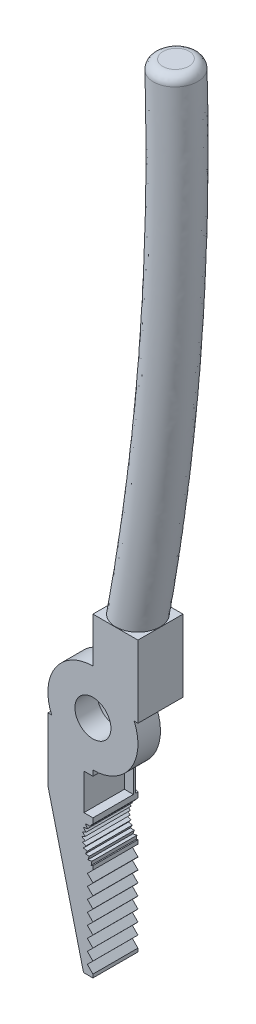
SolidWorks part; units mm, degrees
ref_plane "Front Plane" through (0, 0, 0) normal (0, 0, 1) x (1, 0, 0)
ref_plane "Top Plane" through (0, 0, 0) normal (0, 1, 0) x (1, 0, 0)
ref_plane "Right Plane" through (0, 0, 0) normal (1, 0, 0) x (0, 0, -1)
sketch "Sketch1" plane through (0, 0, 0) normal (0, 0, 1) x (1, 0, 0)
  line L0 (0, -10) -> (0, -20.3897)
  line L1 (0, -50) -> (-2.09, -50)
  line L2 (-10, -18) -> (-10, -4)
  line L3 (0, 10) -> (0, 20)
  line L4 (0, 20) -> (10, 20)
  line L5 (10, 20) -> (10, 4)
  line L6 (-10, -18) -> (-2.09, -50)
  line L7 (14.7669, 4) -> (9.1652, 4)
  line L8 (-10, -4) -> (-9.1652, -4)
  line L9 (0, -49.2488) -> (-1.2488, -48)
  line L10 (-1.2488, -48) -> (0, -46.7512)
  line L11 (-1.2488, -48) -> (0, -48) construction
  line L12 (-1.2449, -45.4965) -> (0.004, -44.2476)
  line L13 (0.004, -46.7453) -> (-1.2449, -45.4965)
  line L14 (-1.2409, -42.993) -> (0.008, -41.7441)
  line L15 (0.008, -44.2418) -> (-1.2409, -42.993)
  line L16 (-1.2369, -40.4894) -> (0.0119, -39.2406)
  line L17 (0.0119, -41.7383) -> (-1.2369, -40.4894)
  line L18 (-1.2329, -37.9859) -> (0.0159, -36.7371)
  line L19 (0.0159, -39.2348) -> (-1.2329, -37.9859)
  line L20 (-1.2289, -35.4824) -> (0.0199, -34.2336)
  line L21 (0.0199, -36.7312) -> (-1.2289, -35.4824)
  line L22 (-1.225, -32.9789) -> (0.0239, -31.73)
  line L23 (0.0239, -34.2277) -> (-1.225, -32.9789)
  line L24 (-1.221, -30.4754) -> (0.0278, -29.2265)
  line L25 (0.0278, -31.7242) -> (-1.221, -30.4754)
  line L26 (0, -31.6963) -> (0, -31.7539)
  line L27 (0, -34.2038) -> (0, -34.2535)
  line L28 (0, -36.7113) -> (0, -36.753)
  line L29 (0, -39.2188) -> (0, -39.2525)
  line L30 (0, -44.2338) -> (0, -44.2516)
  line L31 (0, -41.7263) -> (0, -41.7521)
  line L32 (0, -46.7413) -> (0, -48)
  line L33 (0, -49.2488) -> (0, -50)
  line L35 (-1.6651, -21.1327) -> (-1.2242, -21.903)
  line L36 (-1.6651, -21.1327) -> (-0.6651, -21.1365)
  line L37 (-2.0988, -22.0539) -> (-1.2242, -21.903)
  line L38 (-2.0988, -22.0539) -> (-1.5309, -22.7359)
  line L39 (-2.366, -23.0363) -> (-1.5309, -22.7359)
  line L40 (-2.366, -23.0363) -> (-1.6883, -23.6094)
  line L41 (-2.4585, -24.0503) -> (-1.6883, -23.6094)
  line L42 (-2.4585, -24.0503) -> (-1.6916, -24.4969)
  line L43 (-2.3736, -25.0649) -> (-1.6916, -24.4969)
  line L44 (-2.3736, -25.0649) -> (-1.5407, -25.3715)
  line L45 (-2.1137, -26.0493) -> (-1.5407, -25.3715)
  line L46 (-2.1137, -26.0493) -> (-1.2403, -26.2067)
  line L47 (-1.6869, -26.9737) -> (-1.2403, -26.2067)
  line L48 (-1.6869, -26.9737) -> (-0.7993, -26.977)
  line L49 (-1.106, -27.8098) -> (-0.7993, -26.977)
  line L50 (-1.106, -27.8098) -> (-0.2314, -27.659)
  line L51 (-0.3888, -28.5325) -> (-0.2314, -27.659)
  line L52 (-0.3888, -28.5325) -> (0, -28.3926)
  line L70 (0, -28.3926) -> (0, -29.2544)
  line L71 (7.1202, -28.5604) -> (6.9502, -27.575) [skipped]
  line L72 (6.2873, -28.2538) -> (6.2877, -28.1413) [skipped]
  line L73 (6.2873, -28.2538) -> (6.1818, -28.2149) [skipped]
  line L74 (5.517, -28.6947) -> (5.4198, -28.6381) [skipped]
  line L75 (5.517, -28.6947) -> (5.537, -28.584) [skipped]
  line L76 (4.6819, -28.9951) -> (4.7207, -28.8896) [skipped]
  line L77 (4.6819, -28.9951) -> (4.596, -28.9225) [skipped]
  line L78 (3.8073, -29.146) -> (3.8638, -29.0488) [skipped]
  line L79 (3.8073, -29.146) -> (3.7353, -29.0596) [skipped]
  line L80 (2.9197, -29.1427) -> (2.9923, -29.0568) [skipped]
  line L81 (2.9197, -29.1427) -> (2.8638, -29.0451) [skipped]
  line L82 (2.0462, -28.9853) -> (2.1327, -28.9133) [skipped]
  line L83 (2.0462, -28.9853) -> (2.0082, -28.8795) [skipped]
  line L84 (1.2134, -28.6786) -> (1.311, -28.6228) [skipped]
  line L85 (1.2134, -28.6786) -> (1.1942, -28.5678) [skipped]
  line L86 (0.4464, -28.232) -> (0.4468, -28.1196) [skipped]
  circle A0 centre (0, 0) radius 10
  circle A1 centre (0, 0) radius 4
  arc A2 (-0.6651, -21.1365) -> (0, -20.3897) centre (3.3824, -24.072) cw
  point P114 (3.3824, -24.072)
  dimension "D1" = 20
  dimension "D9" = 8
  dimension "D2" = 40
  dimension "D3" = 45
  dimension "D4" = 2.09
  dimension "D5" = 2
  dimension "D6" = 4
  dimension "D7" = 4
  dimension "D8" = 8
  dimension "D12" = 60
  dimension "D15" = 1
  dimension "D16" = 17
extrude "Boss-Extrude2" add sketch "Sketch1" along normal blind 10 contours A0 L7 L5 L4 L3 | A0 A1 | L36 A2 L0 A0 L8 L2 L6 L1 L33 L9 L10 L32 L13 L12 L30 L15 L14 L31 L17 L16 L29 L19 L18 L28 L21 L20 L27 L23 L22 L26 L25 L24 L70 L52 L51 L50 L49 L48 L47 L46 L45 L44 L43 L42 L41 L40 L39 L38 L37 L35
sketch "Sketch2" plane through (0, 0, 10) normal (0, 0, 1) x (1, 0, 0)
  line L0 (0, -10) -> (0, -20.3897) construction
  line L1 (2, -19.1949) -> (-2, -19.1949)
  line L2 (2, -19.1949) -> (2, -11.1949)
  line L3 (2, -11.1949) -> (-2, -11.1949)
  line L4 (-2, -19.1949) -> (-2, -11.1949)
  line L5 (2, -19.1949) -> (-2, -11.1949) construction
  line L6 (2, -11.1949) -> (-2, -19.1949) construction
  point P0 (0, -15.1949)
  dimension "D1" = 4
  dimension "D2" = 8
extrude "Cut-Extrude1" cut sketch "Sketch2" against normal blind 9
sketch "Sketch3" plane through (0, 0, 0) normal (1, 0, 0) x (0, 0, -1)
  line L0 (0, -10) -> (0, -20.3897) construction
  line L1 (0.5, -19.1949) -> (-0.5, -19.1949)
  line L2 (0.5, -19.1949) -> (0.5, -11.1949)
  line L3 (0.5, -11.1949) -> (-0.5, -11.1949)
  line L4 (-0.5, -19.1949) -> (-0.5, -11.1949)
  line L5 (0.5, -19.1949) -> (-0.5, -11.1949) construction
  line L6 (0.5, -11.1949) -> (-0.5, -19.1949) construction
  point P0 (0, -15.1949)
  dimension "D1" = 8
  dimension "D2" = 1
extrude "Cut-Extrude2" cut sketch "Sketch3" against normal blind 9 draft 21
sketch "Sketch6" plane through (0, 20, 0) normal (0, 1, 0) x (1, 0, 0)
  circle A1 centre (5, -5) radius 4.9307
sketch "Sketch31" plane through (0, 0, 0) normal (0, 0, -1) x (-1, 0, 0)
  circle A0 centre (0, 0) radius 10
extrude "Cut-Extrude3" cut sketch "Sketch31" against normal blind 5
ref_plane "Plane2" through (0, 0, 130) normal (0, 0, 1) x (1, 0, 0)
sketch "Sketch32" plane through (0, 0, 130) normal (0, 0, 1) x (1, 0, 0)
  line L0 (0, 20) -> (0, 140) construction
  line L1 (9.9307, 20) -> (0.0693, 20) construction
  arc A0 (5, 20) -> (13, 140) centre (-497.7978, 113.7865) ccw
  dimension "D3" = 511.47
  dimension "D1" = 120
  dimension "D2" = 13
sweep "Sweep2" add profiles "Sketch6" path "Sketch32"
sketch "Sketch33" plane through (0, 0, 130) normal (0, 0, 1) x (1, 0, 0)
  line L0 (17.7944, 141.1514) -> (8.2056, 138.8486) construction
  line L1 (31.3641, 131.023) -> (-5.3641, 131.023)
  line L2 (31.3641, 131.023) -> (31.3641, 148.977)
  line L3 (31.3641, 148.977) -> (-5.3641, 148.977)
  line L4 (-5.3641, 131.023) -> (-5.3641, 148.977)
  line L5 (31.3641, 131.023) -> (-5.3641, 148.977) construction
  line L6 (31.3641, 148.977) -> (-5.3641, 131.023) construction
  point P0 (13, 140)
extrude "Cut-Extrude4" cut sketch "Sketch33" against normal blind 215
fillet "Fillet1" radius 2 1 edges at (13.0832, 131.023, 0.0786)
